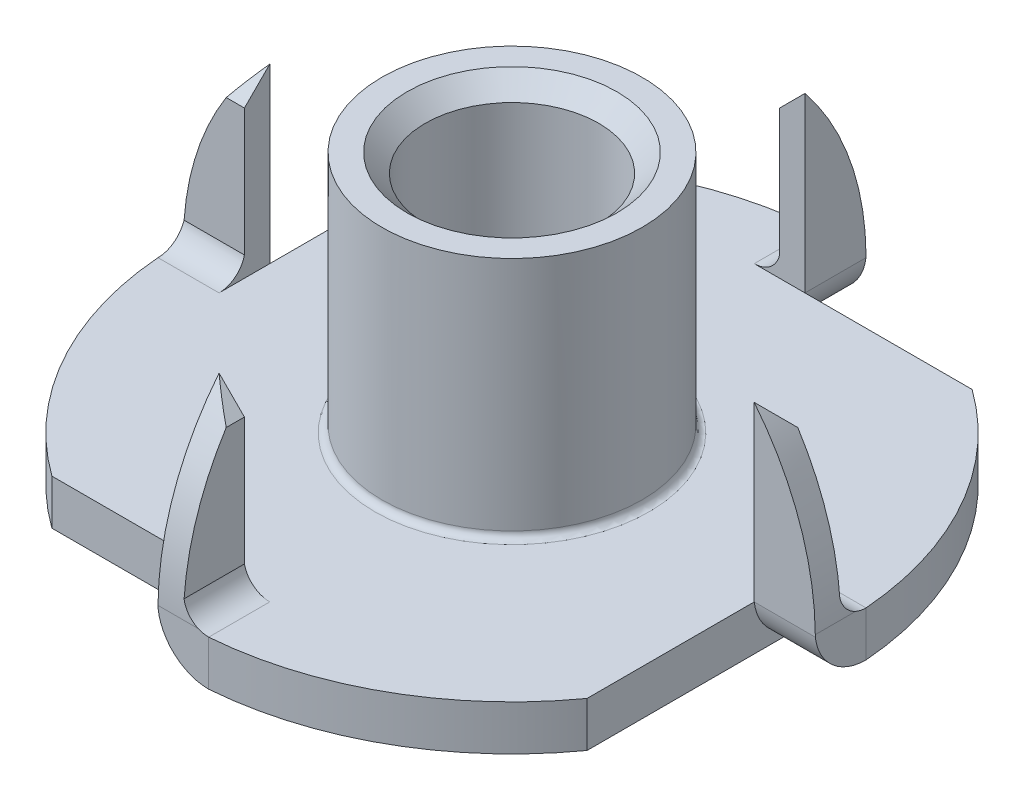
SolidWorks part; units mm, degrees
material "Galvanized Steel"
ref_plane "Front Plane" through (0, 0, 0) normal (0, 0, 1) x (1, 0, 0)
ref_plane "Top Plane" through (0, 0, 0) normal (0, 1, 0) x (1, 0, 0)
ref_plane "Right Plane" through (0, 0, 0) normal (1, 0, 0) x (0, 0, -1)
sketch "Sketch1" plane through (0, 0, 0) normal (0, 1, 0) x (1, 0, 0)
  line L0 (-0.7308, 7.7116) -> (5.5481, 7.7116)
  line L1 (7.7116, 0.7308) -> (7.7116, -5.5481)
  line L2 (0.7308, -7.7116) -> (-5.5481, -7.7116)
  line L3 (-0.7308, 9.4719) -> (-0.7308, 7.7116)
  line L4 (0.7308, -7.7116) -> (0.7308, -9.4719)
  line L5 (-9.4719, -0.7308) -> (-7.7116, -0.7308)
  line L6 (-7.7116, -0.7308) -> (-7.7116, 5.5481)
  line L11 (7.7116, 0.7308) -> (9.4719, 0.7308)
  arc A0 (-0.7308, 9.4719) -> (-7.7116, 5.5481) centre (0, 0) ccw
  arc A1 (-9.4719, -0.7308) -> (-5.5481, -7.7116) centre (0, 0) ccw
  arc A2 (0.7308, -9.4719) -> (7.7116, -5.5481) centre (0, 0) ccw
  arc A3 (9.4719, 0.7308) -> (5.5481, 7.7116) centre (0, 0) ccw
  dimension "D1" = 19
extrude "Boss-Extrude1" add sketch "Sketch1" along normal blind 1.3
sketch "Sketch2" plane through (0, 0, -7.7116) normal (0, 0, -1) x (-1, 0, 0)
  line L0 (-0.7308, 1.3) -> (-0.7308, 6.28)
  line L1 (0, 1.8814) -> (0, 5.5492)
  line L4 (0.7308, 0) -> (0.7308, 1.3)
  line L6 (-0.7308, 6.28) -> (0, 5.5492)
  arc A0 (0.7308, 1.3) -> (0, 1.8814) centre (0.7308, 2.0499) cw
  arc A1 (0.7308, 0) -> (-0.7308, 1.3) centre (0.7308, 1.4716) cw
extrude "Boss-Extrude2" add sketch "Sketch2" along normal blind 1.76
sketch "Sketch3" plane through (0, 0, 0) normal (0, 0, 1) x (1, 0, 0)
  line L0 (0, 4.0175) -> (0, -2.6835) construction
pattern_circular "CirPattern1" count 4 over 360 about axis through (0, 0, 0) along (0, 1, 0) of "Boss-Extrude2"
sketch "Sketch6" plane through (0, 0, 0) normal (1, 0, 0) x (0, 0, -1)
  line L1 (-7.7116, 6.28) -> (-9.4716, 6.28)
  line L2 (-9.4716, 6.28) -> (-9.4719, 1.3)
  line L3 (7.7116, 6.28) -> (9.4716, 6.28)
  line L4 (9.4716, 6.28) -> (9.4719, 1.3)
  arc A0 (-9.4719, 1.3) -> (-7.7116, 6.28) centre (-1.5471, 1.3) cw
  arc A1 (9.4719, 1.3) -> (7.7116, 6.28) centre (1.5471, 1.3) ccw
extrude "Cut-Extrude2" cut sketch "Sketch6" against normal through all and the other way through all
sketch "Sketch7" plane through (0, 0, 0) normal (0, 0, 1) x (1, 0, 0)
  line L0 (-9.4716, 6.28) -> (-7.7116, 6.28)
  line L1 (9.4716, 6.28) -> (7.7116, 6.28)
  line L2 (9.4719, 1.3) -> (9.4716, 6.28)
  line L3 (-9.4719, 1.3) -> (-9.4716, 6.28)
  arc A0 (-9.4719, 1.3) -> (-7.7116, 6.28) centre (-1.5471, 1.3) cw
  arc A1 (9.4719, 1.3) -> (7.7116, 6.28) centre (1.5471, 1.3) ccw
extrude "Cut-Extrude3" cut sketch "Sketch7" against normal through all and the other way through all
sketch "Sketch8" plane through (0, 0, 0) normal (0, 0, 1) x (1, 0, 0)
  line L1 (0, 1.3) -> (0, 8.3)
  line L2 (0, 8.3) -> (3.75, 8.3)
  line L3 (3.75, 8.3) -> (3.75, 1.3)
  line L4 (7.7116, 1.3) -> (0.7308, 1.3) construction
  line L5 (3.75, 1.3) -> (0, 1.3)
  dimension "D1" = 7
  dimension "D2" = 3.75
revolve "Revolve1" add sketch "Sketch8" angle 360 about L1
fillet "Fillet1" radius 0.2 1 edges at (0, 1.3, 3.75)
hole_wizard "M6 Tapped Hole1" positions "Sketch9" profile "Sketch10" tap size "M6" standard "DIN" end condition through all
sketch "Sketch9" plane through (0, 0, 0) normal (0, -1, 0) x (-1, 0, 0)
  point P0 (0, 0)
sketch "Sketch10" plane through (0, 0, 0) normal (1, 0, 0) x (0, 0, -1)
  line L0 (0, 0) -> (0, 8.3)
  line L1 (0, 8.3) -> (3.025, 8.3)
  line L2 (2.5, 7.775) -> (2.5, 0.525)
  line L3 (2.5, 0.525) -> (3.025, 0)
  line L5 (3.025, 0) -> (0, 0)
  line L6 (-2.5, 0.525) -> (-3.025, 0) construction
  line L7 (3.025, 8.3) -> (2.5, 7.775)
  line L8 (-3.025, 8.3) -> (-2.5, 7.775) construction
  line L11 (0, -6.35) -> (0, 107.95) construction
  dimension "Thru Tap Drill Dia." = 5
  dimension "Thru Tap Drill Depth" = 8.3
  dimension "Near C'Sink Dia." = 6.05
  dimension "Near C'Sink Angle" = 90
  dimension "Far C'Sink Dia." = 6.05
  dimension "Far C'Sink Angle" = 90
cosmetic thread "Hole Thread1" parameters "D2"=6
